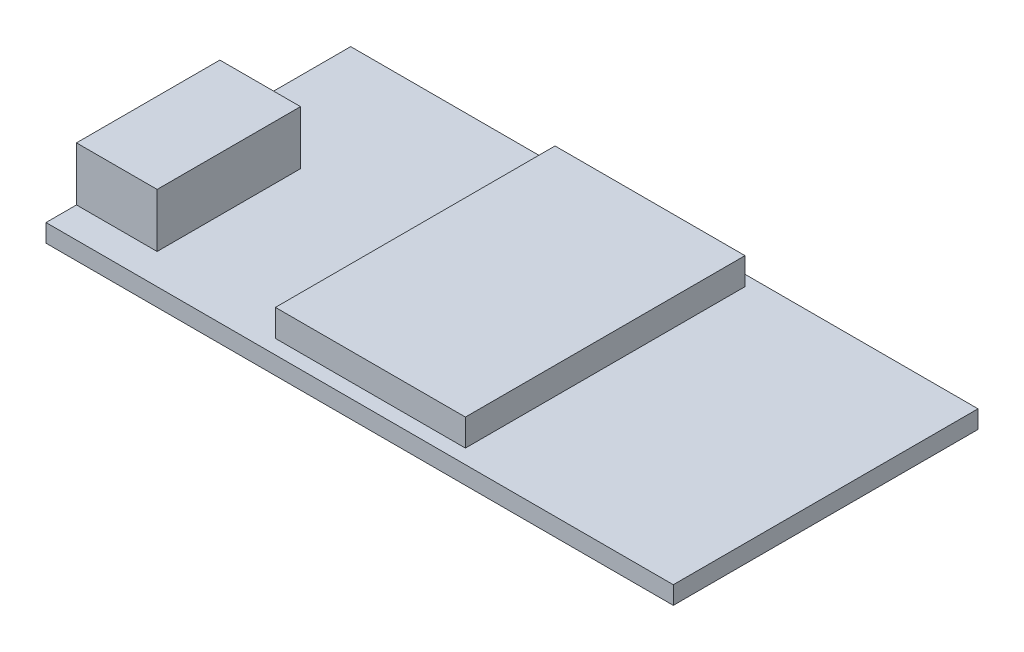
SolidWorks part; units mm, degrees
ref_plane "Front Plane" through (0, 0, 0) normal (0, 0, 1) x (1, 0, 0)
ref_plane "Top Plane" through (0, 0, 0) normal (0, 1, 0) x (1, 0, 0)
ref_plane "Right Plane" through (0, 0, 0) normal (1, 0, 0) x (0, 0, -1)
sketch "Sketch1" plane through (0, 0, 0) normal (0, 1, 0) x (1, 0, 0)
  line L1 (-17.5, -8.5) -> (17.5, -8.5)
  line L2 (-17.5, -8.5) -> (-17.5, 8.5)
  line L3 (-17.5, 8.5) -> (17.5, 8.5)
  line L4 (17.5, -8.5) -> (17.5, 8.5)
  line L5 (-17.5, -8.5) -> (17.5, 8.5) construction
  line L6 (-17.5, 8.5) -> (17.5, -8.5) construction
  point P0 (0, 0)
  dimension "D1" = 17
  dimension "D2" = 35
extrude "Boss-Extrude1" add sketch "Sketch1" along normal mid plane 1
sketch "Sketch2" plane through (0, 0.5, 0) normal (0, 1, 0) x (1, 0, 0)
  line L0 (-17.5, 8.5) -> (-17.5, -8.5) construction
  line L1 (-17.5, -6.8) -> (-13, -6.8)
  line L2 (-17.5, -6.8) -> (-17.5, 1.2)
  line L3 (-17.5, 1.2) -> (-13, 1.2)
  line L4 (-13, -6.8) -> (-13, 1.2)
  line L7 (17.5, 8.5) -> (-17.5, 8.5) construction
  dimension "D1" = 8
  dimension "D2" = 7.3
  dimension "D3" = 4.5
extrude "Boss-Extrude2" add sketch "Sketch2" along normal blind 3
sketch "Sketch3" plane through (0, 0.5, 0) normal (0, 1, 0) x (1, 0, 0)
  line L0 (-17.5, -8.5) -> (17.5, -8.5) construction
  line L1 (-5.5, -7.7) -> (5.1, -7.7)
  line L2 (-5.5, -7.7) -> (-5.5, 7.9)
  line L3 (-5.5, 7.9) -> (5.1, 7.9)
  line L4 (5.1, -7.7) -> (5.1, 7.9)
  line L5 (-17.5, 8.5) -> (-17.5, 1.2) construction
  dimension "D1" = 15.6
  dimension "D2" = 10.6
  dimension "D3" = 0.8
  dimension "D4" = 22.6
extrude "Boss-Extrude3" add sketch "Sketch3" along normal blind 1.5
